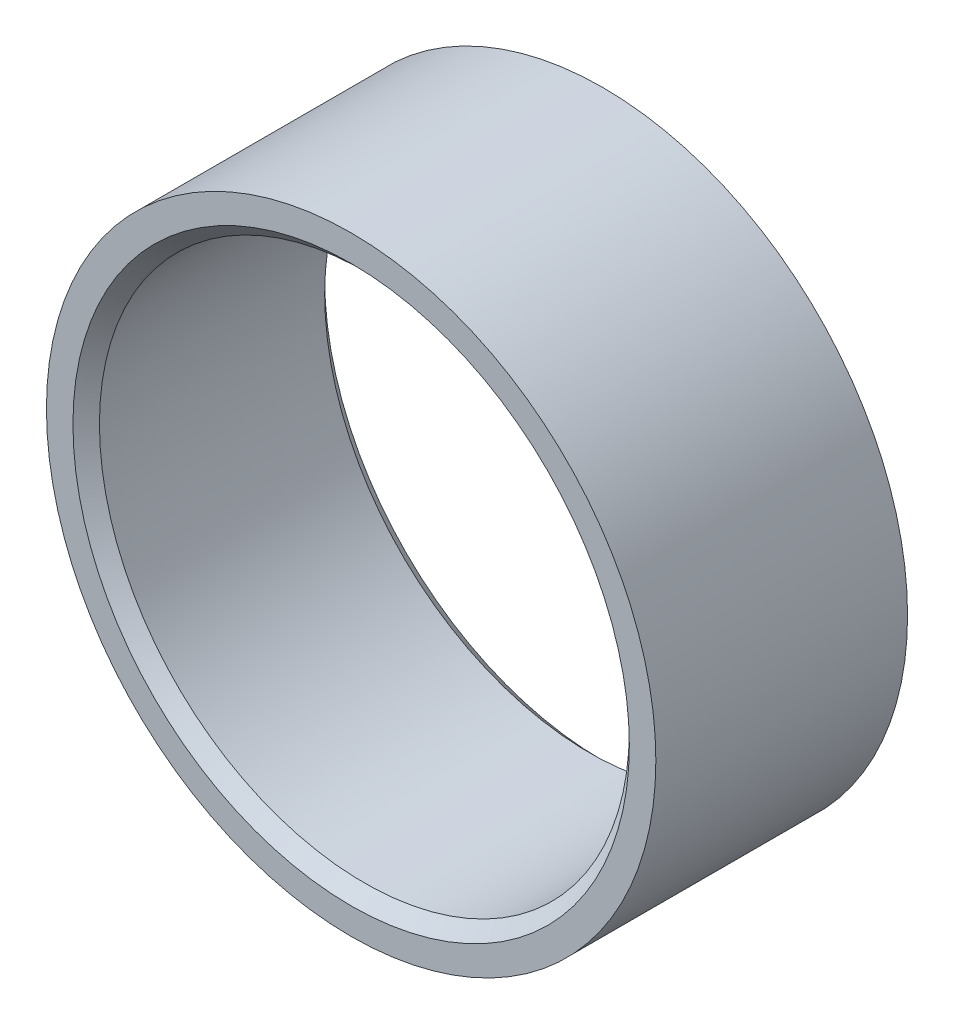
SolidWorks part; units mm, degrees
material "45"
ref_plane "前视基准面" through (0, 0, 0) normal (0, 0, 1) x (1, 0, 0)
ref_plane "上视基准面" through (0, 0, 0) normal (0, 1, 0) x (1, 0, 0)
ref_plane "右视基准面" through (0, 0, 0) normal (1, 0, 0) x (0, 0, -1)
sketch "草图1" plane through (0, 0, 0) normal (0, 0, 1) x (1, 0, 0)
  circle A0 centre (0, 0) radius 11.5
  circle A1 centre (0, 0) radius 10
  dimension "D1" = 20
  dimension "D2" = 23
extrude "凸台-拉伸1" add sketch "草图1" along normal blind 9.5
chamfer "倒角1" distance 0.5 angle 45 2 edges at (10, 0, 0) (10, 0, 9.5)
